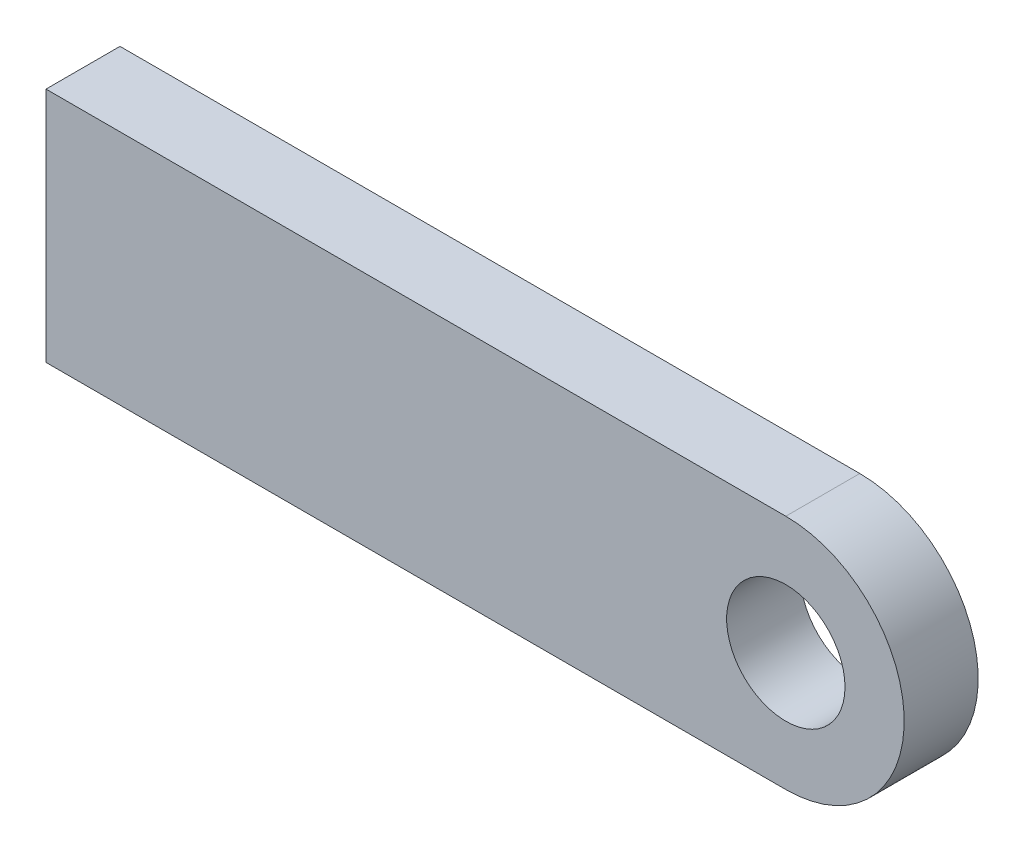
SolidWorks part; units mm, degrees
ref_plane "Front Plane" through (0, 0, 0) normal (0, 0, 1) x (1, 0, 0)
ref_plane "Top Plane" through (0, 0, 0) normal (0, 1, 0) x (1, 0, 0)
ref_plane "Right Plane" through (0, 0, 0) normal (1, 0, 0) x (0, 0, -1)
sketch "Sketch1" plane through (0, 0, 0) normal (0, 0, 1) x (1, 0, 0)
  line L1 (-50, -8) -> (50, -8)
  line L2 (-50, -8) -> (-50, 8) construction
  line L3 (-50, 8) -> (50, 8)
  line L4 (50, -8) -> (50, 8) construction
  line L5 (-50, -8) -> (50, 8) construction
  line L6 (-50, 8) -> (50, -8) construction
  arc A0 (-50, 8) -> (-50, -8) centre (-50, 0) ccw
  arc A1 (50, -8) -> (50, 8) centre (50, 0) ccw
  circle A2 centre (-50, 0) radius 4
  circle A3 centre (50, 0) radius 4
  point P0 (0, 0)
  dimension "D2" = 8
  dimension "D3" = 8
  dimension "D1" = 100
  dimension "D4" = 16
extrude "Boss-Extrude1" add sketch "Sketch1" along normal blind 5
sketch "Sketch2" plane through (0, 0, 0) normal (1, 0, 0) x (0, 0, -1)
  line L1 (-5, 8) -> (0, 8)
  line L2 (-5, 8) -> (-5, -8)
  line L3 (-5, -8) -> (0, -8)
  line L4 (0, 8) -> (0, -8)
extrude "Cut-Extrude1" cut sketch "Sketch2" against normal through all
sketch "Sketch3" plane through (0, 0, 0) normal (-1, 0, 0) x (0, 0, 1)
  line L0 (0, 8) -> (5, -8) construction
  line L1 (0, -8) -> (5, 8) construction
  line L2 (0, 8) -> (5, 8) construction
  line L3 (5, 8) -> (5, -8) construction
  circle A0 centre (2.5, 0) radius 2
  dimension "D1" = 4
extrude "Cut-Extrude3" cut sketch "Sketch3" against normal blind 5
